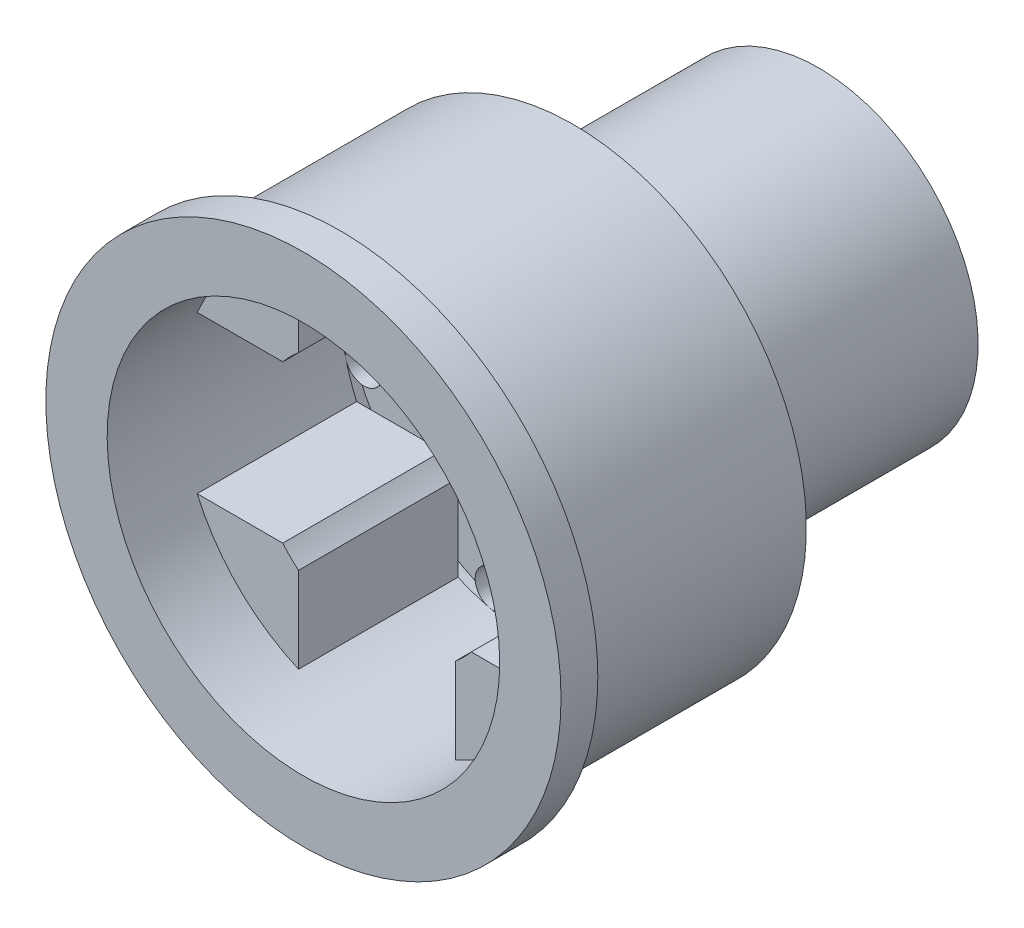
SolidWorks part; units mm, degrees
ref_plane "Спереди" through (0, 0, 0) normal (0, 0, 1) x (1, 0, 0)
ref_plane "Сверху" through (0, 0, 0) normal (0, 1, 0) x (1, 0, 0)
ref_plane "Справа" through (0, 0, 0) normal (1, 0, 0) x (0, 0, -1)
sketch "Sketch1" plane through (0, 0, 0) normal (0, 0, 1) x (1, 0, 0)
  circle A0 centre (0, 0) radius 9.5
  circle A1 centre (0, 0) radius 8
  dimension "D1" = 19
  dimension "D2" = 16
extrude "Extrude1" add sketch "Sketch1" along normal blind 1.5
sketch "Sketch2" plane through (0, 0, 1.5) normal (0, 0, 1) x (1, 0, 0)
  circle A0 centre (0, 0) radius 8 construction
  circle A1 centre (0, 0) radius 10.5
  circle A3 centre (0, 0) radius 8
  dimension "D1" = 21
extrude "Extrude2" add sketch "Sketch2" along normal blind 1.5
sketch "Sketch3" plane through (0, 0, 0) normal (0, 0, -1) x (-1, 0, 0)
  line L0 (0, 3.2) -> (0, -3.2) construction
  line L1 (-7.3321, 3.2) -> (7.3321, 3.2) construction
  line L2 (-7.3321, 3.2) -> (-7.3321, -3.2) construction
  line L3 (-7.3321, -3.2) -> (7.3321, -3.2) construction
  line L4 (7.3321, 3.2) -> (7.3321, -3.2) construction
  line L5 (-7.3321, 3.2) -> (-3.2, 3.2)
  line L6 (-3.2, -7.3321) -> (3.2, -7.3321) construction
  line L7 (-3.2, -7.3321) -> (-3.2, 7.3321) construction
  line L8 (-3.2, 7.3321) -> (3.2, 7.3321) construction
  line L9 (3.2, -7.3321) -> (3.2, 7.3321) construction
  line L10 (-3.2, 3.2) -> (-3.2, 7.3321)
  line L12 (3.2, 7.3321) -> (3.2, 3.2)
  line L13 (3.2, 3.2) -> (7.3321, 3.2)
  line L15 (7.3321, -3.2) -> (3.2, -3.2)
  line L16 (3.2, -3.2) -> (3.2, -7.3321)
  line L18 (-3.2, -7.3321) -> (-3.2, -3.2)
  line L19 (-3.2, -3.2) -> (-7.3321, -3.2)
  circle A0 centre (0, 0) radius 8 construction
  circle A1 centre (0, 0) radius 9.5
  circle A2 centre (0, 0) radius 9.5
  arc A3 (-7.3321, 3.2) -> (-7.3321, -3.2) centre (0, 0) ccw
  arc A4 (3.2, 7.3321) -> (-3.2, 7.3321) centre (0, 0) ccw
  arc A5 (7.3321, -3.2) -> (7.3321, 3.2) centre (0, 0) ccw
  arc A6 (-3.2, -7.3321) -> (3.2, -7.3321) centre (0, 0) ccw
  dimension "D2" = 6.4
  dimension "D1" = 0
extrude "Extrude3" add sketch "Sketch3" along normal blind 6.5
sketch "Sketch4" plane through (0, 0, -6.5) normal (0, 0, -1) x (-1, 0, 0)
  circle A0 centre (0, 0) radius 5
  circle A1 centre (0, 0) radius 9.5 construction
  circle A2 centre (0, 0) radius 9.5
  point P6 (7.3321, 3.2)
  point P9 (3.2, 3.2)
  dimension "D1" = 10
extrude "Extrude4" add sketch "Sketch4" along normal blind 1.5
sketch "Sketch5" plane through (0, 0, -8) normal (0, 0, -1) x (-1, 0, 0)
  circle A0 centre (0, 0) radius 5 construction
  circle A3 centre (0, 0) radius 5
extrude "Extrude5" cut sketch "Sketch5" against normal through all
sketch "Sketch6" plane through (0, 0, -6.5) normal (0, 0, 1) x (1, 0, 0)
  line L0 (0, 0) -> (-4.5, 0) construction
  circle A0 centre (0, 0) radius 5 construction
  circle A1 centre (7.0356, 1.75) radius 0.75
  circle A2 centre (7.0356, -1.75) radius 0.75
  arc A3 (7.3321, -3.2) -> (7.3321, 3.2) centre (0, 0) ccw construction
  dimension "D2" = 1.5
  dimension "D1" = 3.5
extrude "Extrude6" cut sketch "Sketch6" against normal through all
pattern_circular "CirPattern1" count 4 over 360 about axis through (0, 0, 0) along (0, 0, 1) of "Extrude6"
sketch "Sketch7" plane through (0, 0, -8) normal (0, 0, -1) x (-1, 0, 0)
  circle A0 centre (0, 0) radius 5 construction
  circle A1 centre (0, 0) radius 5
  circle A2 centre (0, 0) radius 6.5
  circle A3 centre (1.75, -7.0356) radius 0.75 construction
extrude "Extrude7" add sketch "Sketch7" along normal blind 10
sketch "Sketch8" plane through (0, 0, -18) normal (0, 0, -1) x (-1, 0, 0)
  line L5 (-2.5, 2.5) -> (2.5, 2.5)
  line L6 (-2.5, 2.5) -> (-2.5, -2.5)
  line L7 (-2.5, -2.5) -> (2.5, -2.5)
  line L8 (2.5, 2.5) -> (2.5, -2.5)
  line L9 (-2.5, 2.5) -> (2.5, -2.5) construction
  line L10 (-2.5, -2.5) -> (2.5, 2.5) construction
  circle A0 centre (0, 0) radius 6.5 construction
  circle A1 centre (0, 0) radius 6.5
  point P0 (0, 0)
  dimension "D1" = 5
extrude "Extrude8" add sketch "Sketch8" against normal blind 1.5
